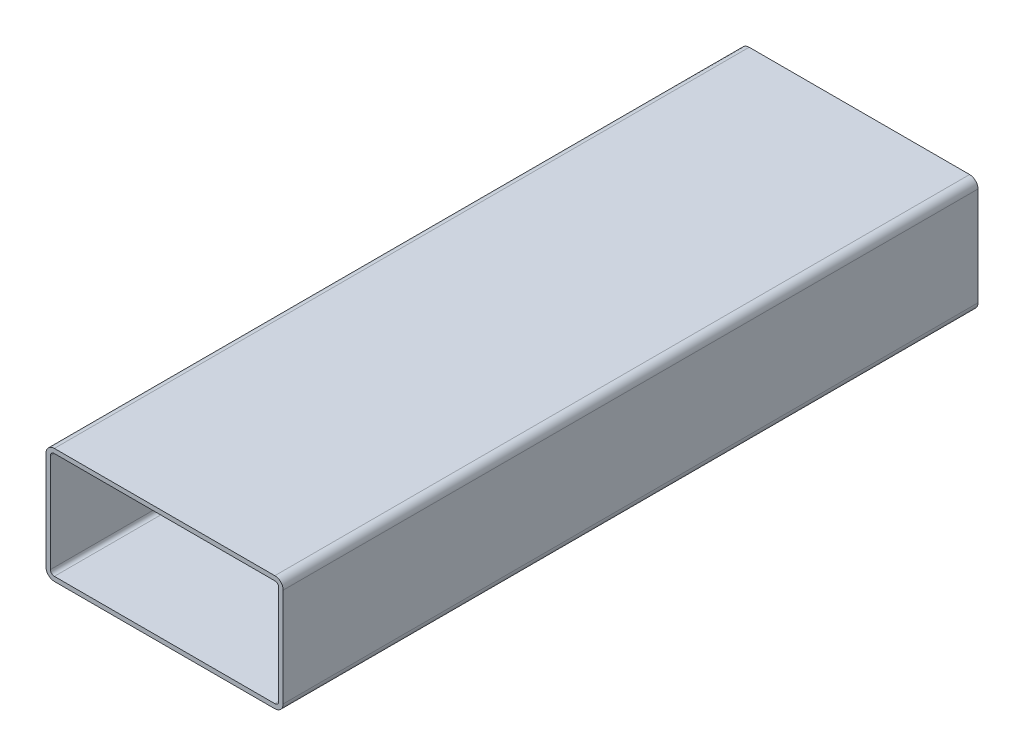
SolidWorks part; units mm, degrees
ref_plane "Front" through (0, 0, 0) normal (0, 0, 1) x (1, 0, 0)
ref_plane "Top" through (0, 0, 0) normal (0, 1, 0) x (1, 0, 0)
ref_plane "Right" through (0, 0, 0) normal (1, 0, 0) x (0, 0, -1)
sketch "Sketch1" plane through (0, 0, 0) normal (0, 0, 1) x (1, 0, 0)
  line L1 (-33, -17.25) -> (33, -17.25)
  line L2 (-35.5, -14.75) -> (-35.5, 14.75)
  line L3 (-33, 17.25) -> (33, 17.25)
  line L4 (35.5, -14.75) -> (35.5, 14.75)
  line L5 (-35.5, -17.25) -> (35.5, 17.25) construction
  line L6 (-35.5, 17.25) -> (35.5, -17.25) construction
  arc A0 (33, -17.25) -> (35.5, -14.75) centre (33, -14.75) ccw
  arc A1 (-35.5, 14.75) -> (-33, 17.25) centre (-33, 14.75) cw
  arc A2 (-33, -17.25) -> (-35.5, -14.75) centre (-33, -14.75) cw
  arc A3 (33, 17.25) -> (35.5, 14.75) centre (33, 14.75) cw
  point P0 (0, 0)
  dimension "D3" = 2.5
  dimension "D1" = 71
  dimension "D2" = 34.5
extrude "Boss-Extrude1" add sketch "Sketch1" against normal blind 208
shell "Shell1" thickness 1.33
